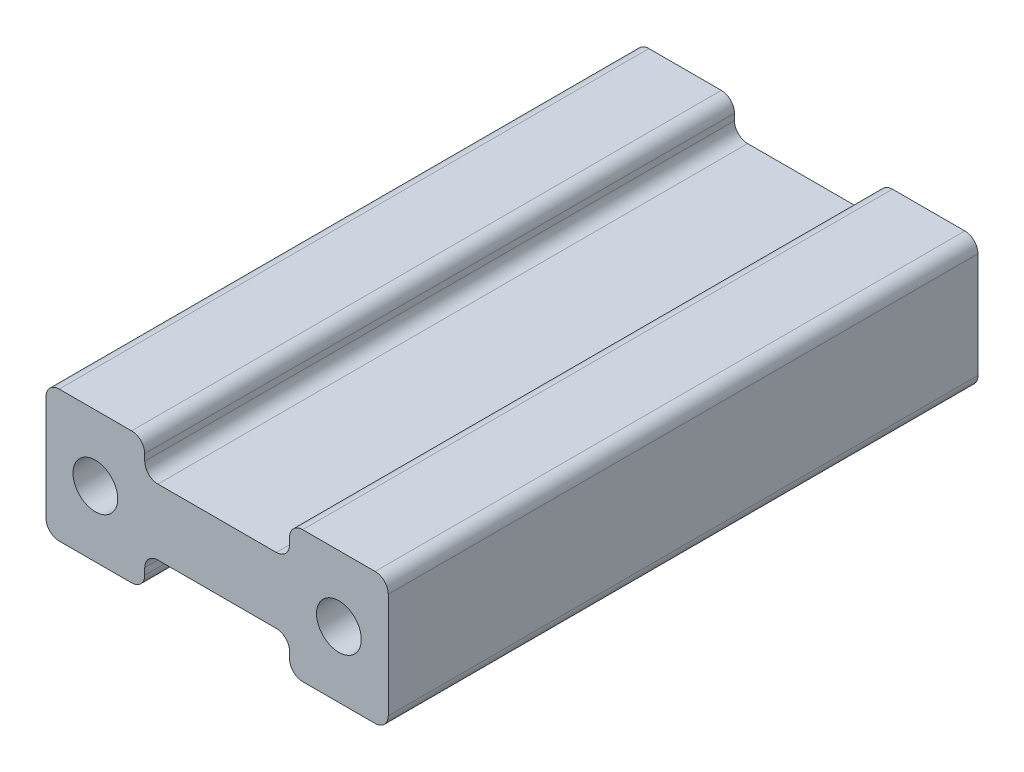
SolidWorks part; units mm, degrees
material "ABS"
ref_plane "Alzado" through (0, 0, 0) normal (1, 0, 0) x (0, 1, 0)
ref_plane "Planta" through (0, 0, 0) normal (0, 0, 1) x (0, 1, 0)
ref_plane "Vista lateral" through (0, 0, 0) normal (0, 1, 0) x (-1, 0, 0)
sketch "Croquis1" plane through (0, 0, 0) normal (0, 0, 1) x (0, 1, 0)
  line L0 (0, 0) -> (10.1993, 0) construction
  line L1 (0, 0) -> (0, 13) construction
  line L2 (-5, 13) -> (5, 13)
  line L7 (5, 13) -> (5, 5.5)
  line L8 (5, 5.5) -> (2.5, 5.5)
  line L9 (2.5, 5.5) -> (2.5, -5.5)
  line L10 (-2.5, 5.5) -> (-2.5, -5.5)
  line L11 (-5, 5.5) -> (-2.5, 5.5)
  line L12 (-5, 13) -> (-5, 5.5)
  line L13 (5, -13) -> (5, -5.5)
  line L14 (5, -5.5) -> (2.5, -5.5)
  line L15 (-5, -5.5) -> (-2.5, -5.5)
  line L16 (-5, -13) -> (5, -13)
  line L17 (-5, -13) -> (-5, -5.5)
  point P14 (-2.5, 0)
  point P15 (2.5, 0)
  dimension "D1" = 13
  dimension "D2" = 5
  dimension "D3" = 2.5
  dimension "D4" = 7.5
extrude "Saliente-Extruir1" add sketch "Croquis1" along normal mid plane 44.8
fillet "Redondeo1" radius 1 12 edges at (5.5, -2.5, 0) (5.5, -5, 0) (-5.5, -5, 0) (-5.5, -2.5, 0) (-5.5, 2.5, 0) (-5.5, 5, 0) (13, 5, 0) (5.5, 5, 0) (5.5, 2.5, 0) (13, -5, 0) (-13, -5, 0) (-13, 5, 0)
sketch "Croquis2" plane through (0, 0, -22.4) normal (0, 0, -1) x (1, 0, 0)
  line L0 (-13, 0) -> (13, 0) construction
  line L1 (-13, -4) -> (-13, 4) construction
  line L2 (13, 4) -> (13, -4) construction
  line L3 (0, 7.565) -> (0, 0) construction
  point P9 (-9.25, 0)
  point P10 (0, 0)
  point P11 (9.25, 0)
  dimension "D1" = 9.25
hole_wizard "Taladro de margen para M31" positions "Croquis2" profile "Croquis3" hole size "M3" standard "Ansi Metric" end condition through all
sketch "Croquis3" plane through (9.25, 0, -22.4) normal (1, 0, 0) x (0, 1, 0)
  line L0 (0, 0) -> (0, 44.8)
  line L1 (0, 44.8) -> (1.7, 44.8)
  line L2 (1.7, 44.8) -> (1.7, 0)
  line L5 (1.7, 0) -> (0, 0)
  line L11 (0, -6.35) -> (0, 107.95) construction
  dimension "Diámetro de taladro hasta el siguiente" = 3.4
  dimension "Profundidad de taladro hasta el siguiente" = 44.8
